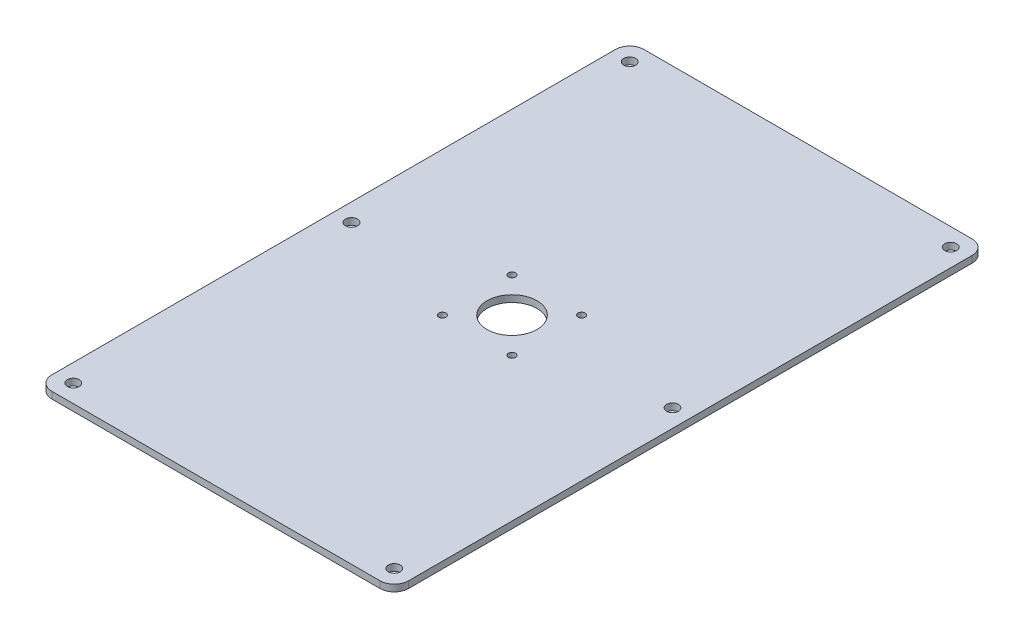
SolidWorks part; units mm, degrees
material "ABS"
ref_plane "Front Plane" through (0, 0, 0) normal (0, 0, 1) x (1, 0, 0)
ref_plane "Top Plane" through (0, 0, 0) normal (0, 1, 0) x (1, 0, 0)
ref_plane "Right Plane" through (0, 0, 0) normal (1, 0, 0) x (0, 0, -1)
sketch "Sketch1" plane through (0, 0, 0) normal (0, 1, 0) x (1, 0, 0)
  line L1 (-79.375, -131.7625) -> (79.375, -131.7625)
  line L2 (-79.375, -131.7625) -> (-79.375, 131.7625)
  line L3 (-79.375, 131.7625) -> (79.375, 131.7625)
  line L4 (79.375, -131.7625) -> (79.375, 131.7625)
  line L5 (-79.375, -131.7625) -> (79.375, 131.7625) construction
  line L6 (-79.375, 131.7625) -> (79.375, -131.7625) construction
  point P0 (0, 0)
  dimension "D1" = 158.75
  dimension "D2" = 263.525
extrude "Boss-Extrude1" add sketch "Sketch1" along normal blind 3
sketch "Sketch5" plane through (0, 3, 0) normal (0, 1, 0) x (1, 0, 0)
  circle A0 centre (0, 0) radius 11.1125
  dimension "D1" = 22.225
extrude "Cut-Extrude1" cut sketch "Sketch5" against normal through all
hole_wizard "M3 Clearance Hole1" positions "Sketch6" profile "Sketch7" hole size "M3" standard "ANSI Metric" end condition up to next
sketch "Sketch6" plane through (0, 3, 0) normal (0, 1, 0) x (1, 0, 0)
  line L1 (-15.5, -15.5) -> (15.5, -15.5) construction
  line L2 (-15.5, -15.5) -> (-15.5, 15.5) construction
  line L3 (-15.5, 15.5) -> (15.5, 15.5) construction
  line L4 (15.5, -15.5) -> (15.5, 15.5) construction
  line L5 (-15.5, -15.5) -> (15.5, 15.5) construction
  line L6 (-15.5, 15.5) -> (15.5, -15.5) construction
  point P0 (0, 0)
  point P1 (15.5, 15.5)
  point P68 (-15.5, -15.5)
  point P69 (-15.5, 15.5)
  point P70 (15.5, -15.5)
  dimension "D1" = 31
sketch "Sketch7" plane through (0, 3, 0) normal (1, 0, 0) x (0, 0, 1)
  line L0 (0, 0) -> (0, 3)
  line L1 (0, 3) -> (1.6, 3)
  line L2 (1.6, 3) -> (1.6, 0)
  line L5 (1.6, 0) -> (0, 0)
  line L11 (0, -6.35) -> (0, 107.95) construction
  dimension "Thru Hole Dia." = 3.2
  dimension "Thru Hole Depth" = 3
hole_wizard "M5 Clearance Hole2" positions "Sketch8" profile "Sketch9" hole size "M5" standard "ANSI Metric" end condition up to next
sketch "Sketch8" plane through (0, 3, 0) normal (0, 1, 0) x (1, 0, 0)
  line L1 (-71.4375, -123.825) -> (71.4375, -123.825) construction
  line L2 (-71.4375, -123.825) -> (-71.4375, 123.825) construction
  line L3 (-71.4375, 123.825) -> (71.4375, 123.825) construction
  line L4 (71.4375, -123.825) -> (71.4375, 123.825) construction
  line L5 (-71.4375, -123.825) -> (71.4375, 123.825) construction
  line L6 (-71.4375, 123.825) -> (71.4375, -123.825) construction
  point P1 (0, 0)
  point P2 (71.4375, 123.825)
  point P143 (-71.4375, -123.825)
  point P144 (-71.4375, 123.825)
  point P145 (71.4375, -123.825)
  point P156 (-71.4375, 0)
  point P158 (71.4375, 0)
  dimension "D1" = 247.65
  dimension "D2" = 142.875
sketch "Sketch9" plane through (0, 3, 0) normal (1, 0, 0) x (0, 0, 1)
  line L0 (0, 0) -> (0, 3)
  line L1 (0, 3) -> (2.65, 3)
  line L2 (2.65, 3) -> (2.65, 0)
  line L5 (2.65, 0) -> (0, 0)
  line L11 (0, -6.35) -> (0, 107.95) construction
  dimension "Thru Hole Dia." = 5.3
  dimension "Thru Hole Depth" = 3
fillet "Fillet1" radius 6.35 4 edges at (79.375, 1.5, 131.7625) (-79.375, 1.5, -131.7625) (79.375, 1.5, -131.7625) (-79.375, 1.5, 131.7625)
